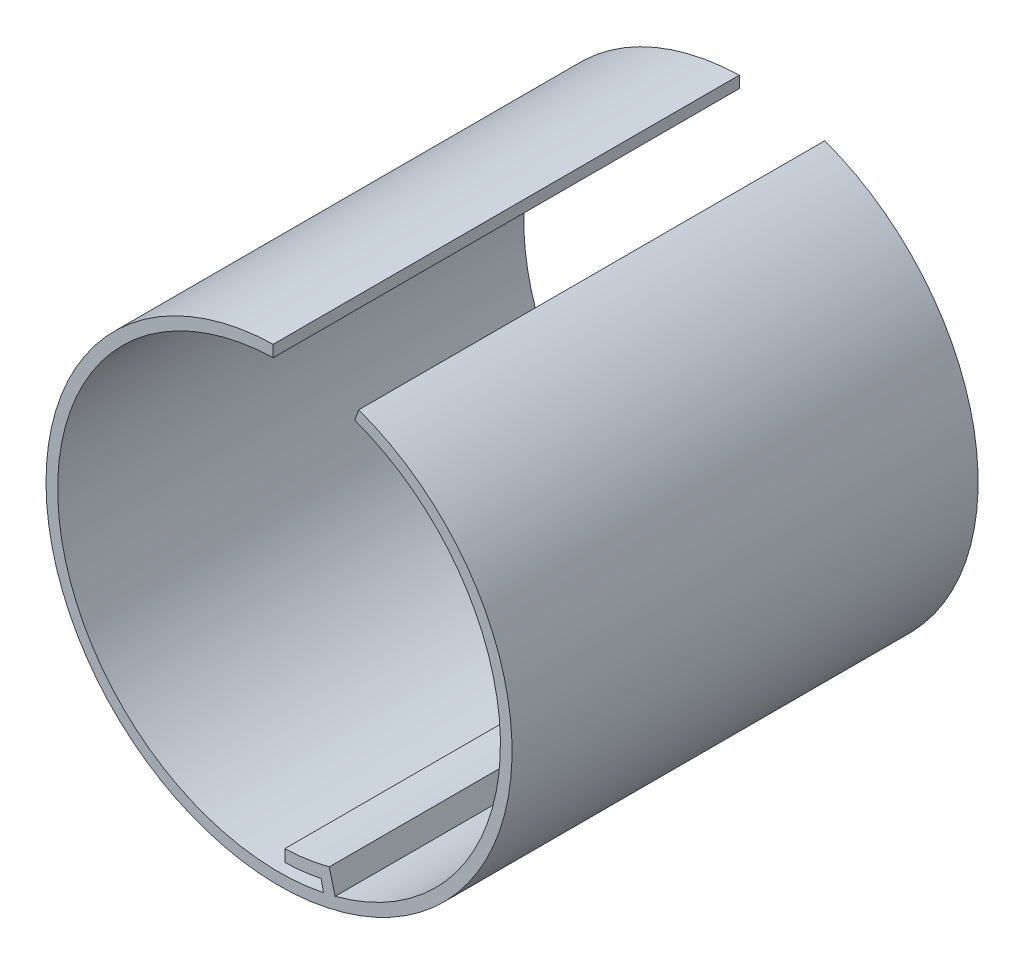
SolidWorks part; units mm, degrees
material "1060 Alloy"
ref_plane "Front Plane" through (0, 0, 0) normal (0, 0, 1) x (1, 0, 0)
ref_plane "Top Plane" through (0, 0, 0) normal (0, 1, 0) x (1, 0, 0)
ref_plane "Right Plane" through (0, 0, 0) normal (1, 0, 0) x (0, 0, -1)
sketch "Sketch1" plane through (0, 0, 0) normal (0, 0, 1) x (1, 0, 0)
  line L0 (-1.27, 50.7841) -> (-1.27, 48.2433)
  line L1 (-0.3967, 0) -> (-50000.3967, 0) construction
  line L2 (16.5059, 45.3496) -> (17.3746, 47.7364)
  line L7 (9.2012, -44.8598) -> (9.6967, -47.2758)
  line L9 (10.9466, -41.7694) -> (12.2345, -46.6835)
  line L11 (1.27, -43.1613) -> (1.27, -45.7761)
  arc A3 (0, -48.26) -> (9.6967, -47.2758) centre (0, 0) ccw
  arc A4 (1.27, -45.7761) -> (9.2012, -44.8598) centre (0, 0) ccw
  arc A5 (0, -48.26) -> (-1.27, 48.2433) centre (0, 0) cw
  arc A6 (1.27, -43.1613) -> (10.9466, -41.7694) centre (0, 0) ccw
  arc A8 (-1.27, 50.7841) -> (17.3746, 47.7364) centre (0, 0) ccw
  arc A9 (12.2345, -46.6835) -> (16.5059, 45.3496) centre (0, 0) ccw
  point P4 (0, 0)
  point P10 (0, 0)
  dimension "D1" = 45.7937
  dimension "D2" = 43.18
  dimension "D5" = 2.6148
  dimension "D8" = 48.26
  dimension "D6" = 9.2012
  dimension "D4" = 1.27
  dimension "D3" = 50.8
  dimension "D7" = 10.9466
  dimension "D9" = 16.5059
  dimension "D12" = 1.27
extrude "Boss-Extrude1" add sketch "Sketch1" along normal blind 101.6
